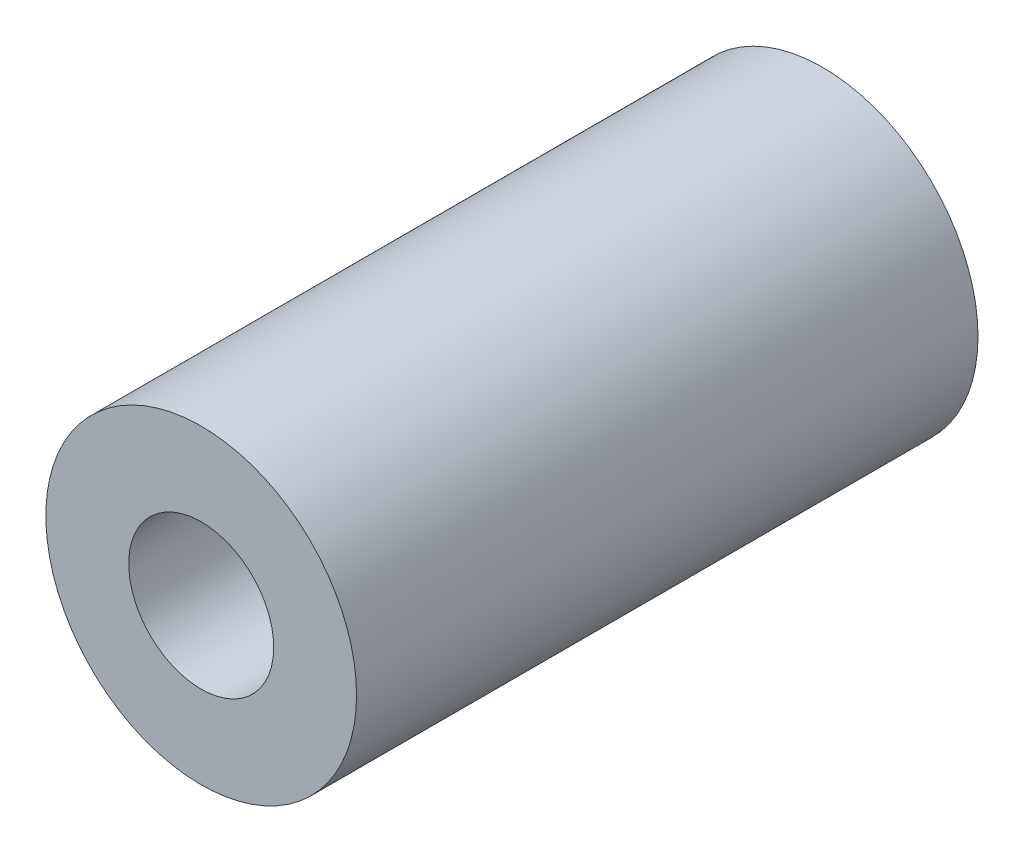
SolidWorks part; units mm, degrees
ref_plane "Front Plane" through (0, 0, 0) normal (0, 0, 1) x (1, 0, 0)
ref_plane "Top Plane" through (0, 0, 0) normal (0, 1, 0) x (1, 0, 0)
ref_plane "Right Plane" through (0, 0, 0) normal (1, 0, 0) x (0, 0, -1)
sketch "Sketch1" plane through (0, 0, 0) normal (0, 0, 1) x (1, 0, 0)
  circle A1 centre (0, 0) radius 1.75
  circle A2 centre (0, 0) radius 3.75
  dimension "D1" = 3.5
  dimension "D2" = 2
extrude "Boss-Extrude1" add sketch "Sketch1" along normal blind 15
